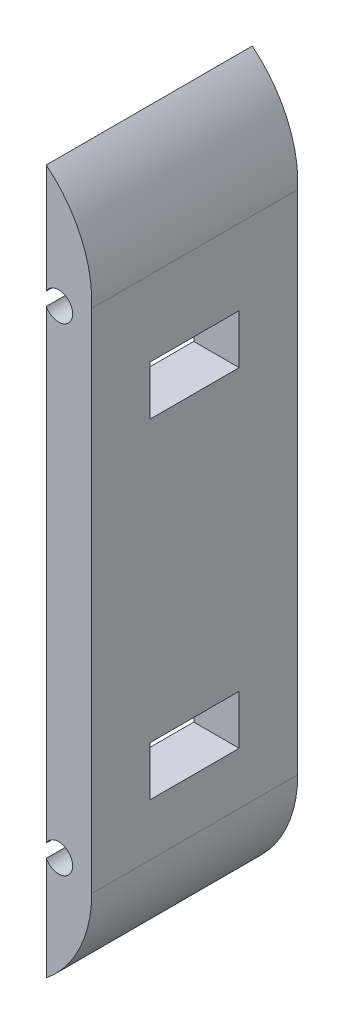
SolidWorks part; units mm, degrees
ref_plane "Plan de face" through (0, 0, 0) normal (0, 0, 1) x (1, 0, 0)
ref_plane "Plan de dessus" through (0, 0, 0) normal (0, 1, 0) x (1, 0, 0)
ref_plane "Plan de droite" through (0, 0, 0) normal (1, 0, 0) x (0, 0, -1)
sketch "Esquisse1" plane through (0, 0, 0) normal (0, 0, 1) x (1, 0, 0)
  line L0 (-2.5153, 35.459) -> (-2.5153, 31.759)
  line L5 (3, -28.8) -> (3, 32.7)
  line L7 (-2.5153, -27.841) -> (-2.5153, -40.4207)
  line L12 (-2.5153, 30.159) -> (-2.5153, -26.241)
  line L14 (-2.5153, 35.459) -> (-2.5153, 45.0203)
  arc A0 (-2.5153, 30.159) -> (-2.5153, 31.759) centre (-1.0153, 30.959) ccw
  arc A1 (-2.5153, -27.841) -> (-2.5153, -26.241) centre (-1.0153, -27.041) ccw
  arc A3 (3, -28.8) -> (-2.5153, -40.4207) centre (-12, -28.8) cw
  arc A6 (3, 32.7) -> (-2.5153, 45.0203) centre (-11.9843, 33.3868) ccw
  point P6 (0, 0)
  point P12 (-12, -37.7953)
  dimension "D2" = 3.4
  dimension "D8" = 15
  dimension "D10" = 61.5
extrude "Boss.-Extru.1" add sketch "Esquisse1" along normal blind 25
sketch "Esquisse6" plane through (3, 0, 0) normal (1, 0, 0) x (0, 0, -1)
  line L0 (0, 20.5243) -> (-25, 20.5243) construction
  line L1 (-7.1, 17.5243) -> (-17.9, 17.5243)
  line L2 (-7.1, 17.5243) -> (-7.1, 23.5243)
  line L3 (-7.1, 23.5243) -> (-17.9, 23.5243)
  line L4 (-17.9, 17.5243) -> (-17.9, 23.5243)
  line L5 (-7.1, 17.5243) -> (-17.9, 23.5243) construction
  line L6 (-7.1, 23.5243) -> (-17.9, 17.5243) construction
  line L7 (-25, -28.8) -> (-25, 32.7) construction
  line L8 (0, -28.8) -> (0, 32.7) construction
  line L9 (-25, 1.95) -> (10.1658, 1.95) construction
  line L14 (0, -19.4757) -> (-25, -19.4757) construction
  line L19 (0, -28.8) -> (0, 32.7) construction
  line L24 (-12.5, -19.4757) -> (-12.5, 20.5243) construction
  line L25 (-7.1, -22.4757) -> (-17.9, -22.4757)
  line L26 (-7.1, -22.4757) -> (-7.1, -16.4757)
  line L27 (-7.1, -16.4757) -> (-17.9, -16.4757)
  line L28 (-17.9, -22.4757) -> (-17.9, -16.4757)
  line L29 (-7.1, -22.4757) -> (-17.9, -16.4757) construction
  line L30 (-7.1, -16.4757) -> (-17.9, -22.4757) construction
  point P0 (-12.5, 20.5243)
  point P11 (-12.5, 20.5243)
  point P15 (-12.5, -19.4757)
  point P21 (-12.5, -19.4757)
  dimension "D1" = 6
  dimension "D2" = 10.8
  dimension "D3" = 6
  dimension "D4" = 10.8
  dimension "D5" = 40
extrude "Enlèv. mat.-Extru.5" cut sketch "Esquisse6" against normal blind 16
